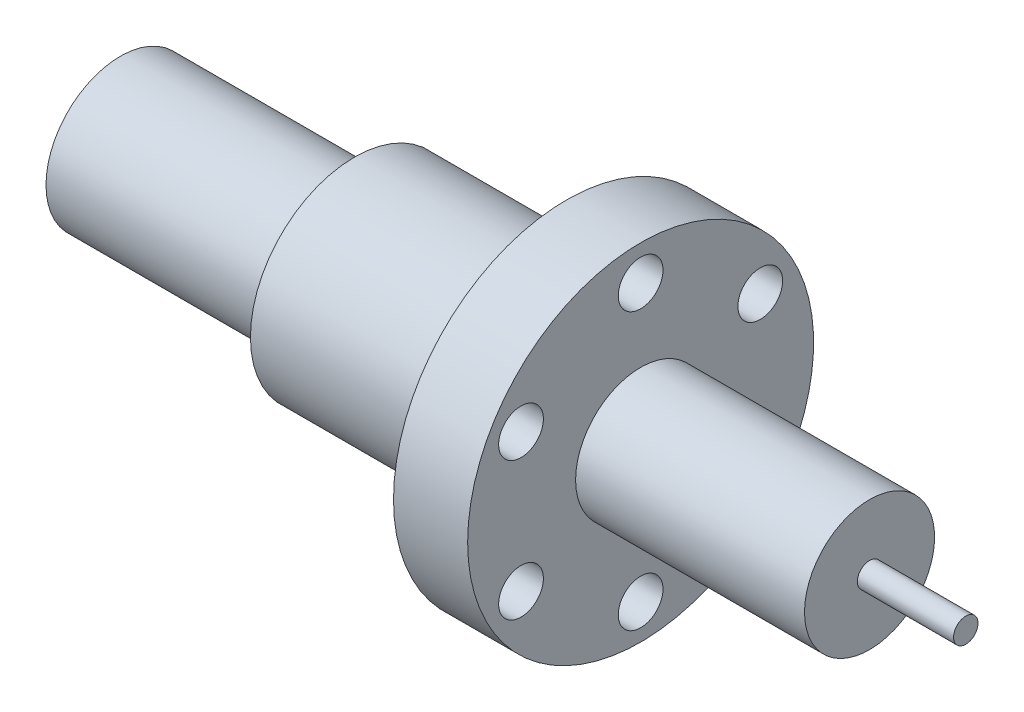
SolidWorks part; units mm, degrees
ref_plane "Front Plane" through (0, 0, 0) normal (0, 0, 1) x (1, 0, 0)
ref_plane "Top Plane" through (0, 0, 0) normal (0, 1, 0) x (1, 0, 0)
ref_plane "Right Plane" through (0, 0, 0) normal (1, 0, 0) x (0, 0, -1)
sketch "Sketch1" plane through (0, 0, 0) normal (0, 0, 1) x (1, 0, 0)
  line L0 (-40.7284, 0) -> (47.2697, 0) construction
  line L1 (31.75, 0) -> (31.75, 1.1938)
  line L2 (31.75, 1.1938) -> (22.352, 1.1938)
  line L3 (22.352, 1.1938) -> (22.352, 6.35)
  line L4 (22.352, 6.35) -> (0, 6.35)
  line L5 (0, 6.35) -> (0, 16.891)
  line L6 (0, 16.891) -> (-7.239, 16.891)
  line L7 (-7.239, 16.891) -> (-7.239, 10.16)
  line L8 (-7.239, 10.16) -> (-50.8, 10.16)
  line L9 (-50.8, 10.16) -> (-50.8, 0)
  line L10 (-50.8, 0) -> (31.75, 0)
  dimension "D1" = 2.3876
  dimension "D2" = 12.7
  dimension "D3" = 20.32
  dimension "D4" = 50.8
  dimension "D5" = 31.75
  dimension "D6" = 9.398
  dimension "D7" = 33.782
  dimension "D8" = 7.239
revolve "Revolve1" add sketch "Sketch1" angle 360 about L0
sketch "Sketch2" plane through (0, 0, 0) normal (1, 0, 0) x (0, 0, -1)
  circle A0 centre (0, 13.4874) radius 2.1844
  dimension "D1" = 4.3688
  dimension "D2" = 13.4874
extrude "Extrude1" cut sketch "Sketch2" against normal through all
pattern_circular "CirPattern1" count 6 over 360 about axis through (0, 0, 0) along (1, 0, 0) of "Extrude1"
sketch "Sketch3" plane through (-50.8, 0, 0) normal (-1, 0, 0) x (0, 0, 1)
  circle A0 centre (0, 0) radius 7.2611
  circle A1 centre (0, 0) radius 10.16
extrude "Extrude2" cut sketch "Sketch3" against normal blind 22.86
